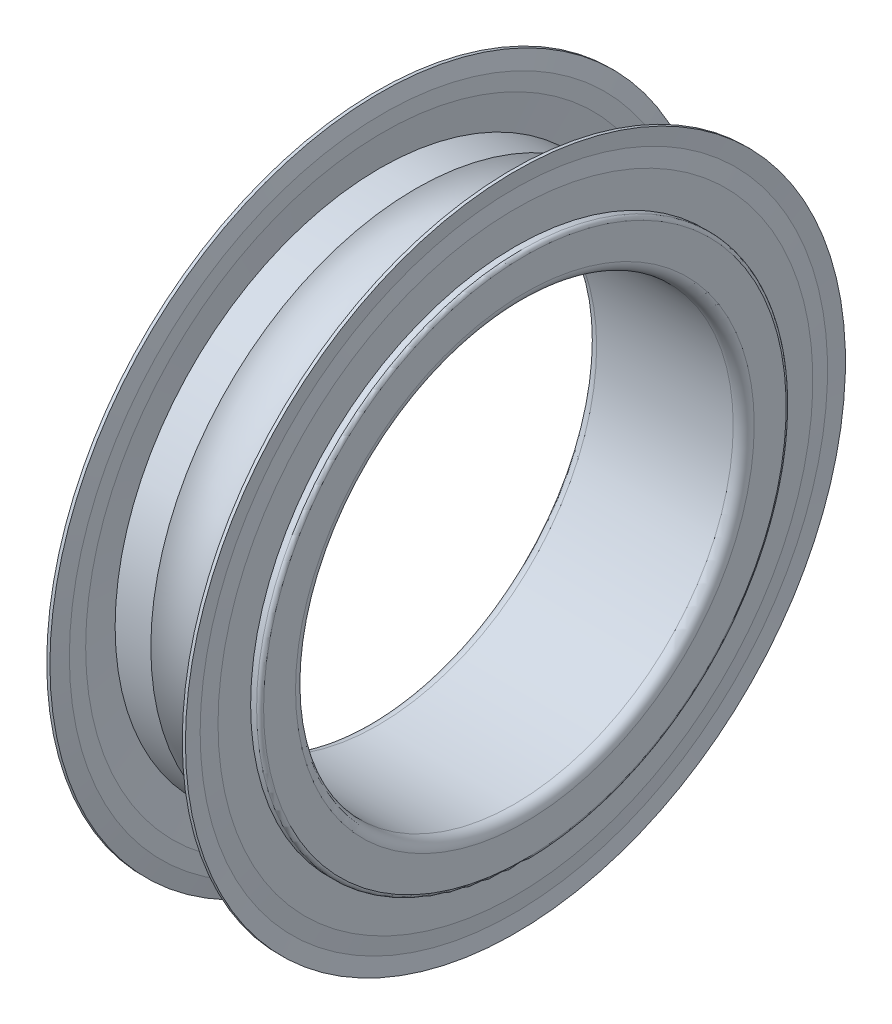
SolidWorks part; units mm, degrees
ref_plane "Front Plane" through (0, 0, 0) normal (0, 0, 1) x (1, 0, 0)
ref_plane "Top Plane" through (0, 0, 0) normal (0, 1, 0) x (1, 0, 0)
ref_plane "Right Plane" through (0, 0, 0) normal (1, 0, 0) x (0, 0, -1)
ref_plane "Plane1" through (0, 0, 0) normal (0, 0, 1) x (1, 0, 0)
sketch "Sketch1" plane through (0, 0, 0) normal (0, 0, 1) x (1, 0, 0)
  line L0 (0, 14.925) -> (0, 13.1)
  line L1 (0.6, 12.5) -> (8.4, 12.5)
  line L2 (9, 13.1) -> (9, 14.925)
  line L3 (8.8, 15.125) -> (6.2403, 15.125)
  line L4 (2.7597, 15.125) -> (0.2, 15.125)
  line L5 (50, 0) -> (-50, 0) construction
  arc A0 (0, 13.1) -> (0.6, 12.5) centre (0.6, 13.1) ccw
  arc A1 (8.4, 12.5) -> (9, 13.1) centre (8.4, 13.1) ccw
  arc A2 (9, 14.925) -> (8.8, 15.125) centre (8.8, 14.925) ccw
  arc A3 (6.2403, 15.125) -> (2.7597, 15.125) centre (4.5, 16.75) cw
  arc A4 (0.2, 15.125) -> (0, 14.925) centre (0.2, 14.925) ccw
revolve "Revolve1" add sketch "Sketch1" angle 360 about L5
ref_plane "Plane2" through (0, 0, 0) normal (0, 0, 1) x (1, 0, 0)
sketch "Sketch2" plane through (0, 0, 0) normal (0, 0, 1) x (1, 0, 0)
  line L0 (0.54, 18.85) -> (0.63, 17.9187)
  line L1 (0.63, 17.9187) -> (0.54, 16.9875)
  line L2 (0.54, 16.9875) -> (0.54, 15.125)
  line L3 (0.54, 15.125) -> (0.72, 15.125)
  line L4 (0.72, 15.125) -> (0.9, 16.9875)
  line L5 (0.9, 16.9875) -> (0.9, 17.9187)
  line L6 (0.9, 17.9187) -> (0.72, 18.85)
  line L7 (0.72, 18.85) -> (0.54, 18.85)
  line L8 (50, 0) -> (-50, 0) construction
revolve "Revolve2" add sketch "Sketch2" angle 360 about L8
ref_plane "Plane3" through (0, 0, 0) normal (0, 0, 1) x (1, 0, 0)
sketch "Sketch3" plane through (0, 0, 0) normal (0, 0, 1) x (1, 0, 0)
  line L0 (8.1, 16.9875) -> (8.28, 15.125)
  line L1 (8.28, 15.125) -> (8.46, 15.125)
  line L2 (8.46, 15.125) -> (8.46, 16.9875)
  line L3 (8.46, 16.9875) -> (8.37, 17.9187)
  line L4 (8.37, 17.9187) -> (8.46, 18.85)
  line L5 (8.46, 18.85) -> (8.28, 18.85)
  line L6 (8.28, 18.85) -> (8.1, 17.9187)
  line L7 (8.1, 17.9187) -> (8.1, 16.9875)
  line L8 (50, 0) -> (-50, 0) construction
revolve "Revolve3" add sketch "Sketch3" angle 360 about L8
